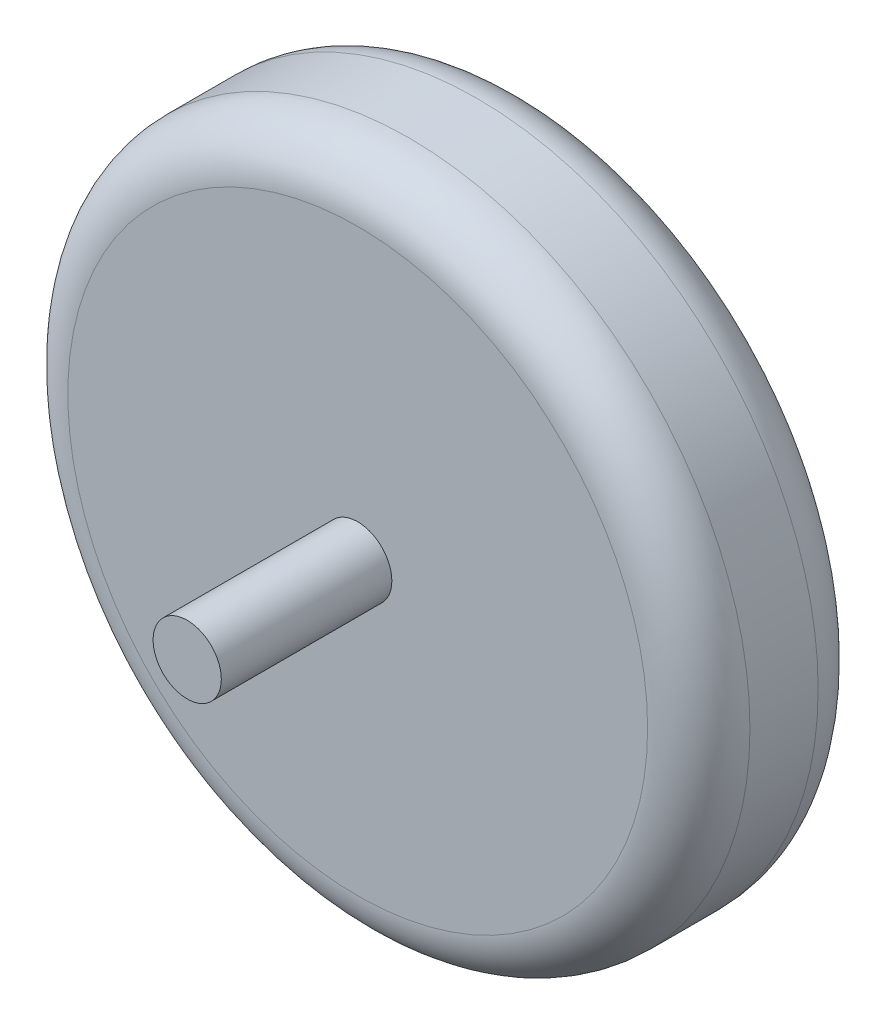
SolidWorks part; units mm, degrees
ref_plane "前视基准面" through (0, 0, 0) normal (0, 0, 1) x (1, 0, 0)
ref_plane "上视基准面" through (0, 0, 0) normal (0, 1, 0) x (1, 0, 0)
ref_plane "右视基准面" through (0, 0, 0) normal (1, 0, 0) x (0, 0, -1)
other "Configuration Table"
sketch "草图1" plane through (0, 0, 0) normal (0, 0, 1) x (1, 0, 0)
  circle A0 centre (0, 0) radius 100
extrude "凸台-拉伸1" add sketch "草图1" along normal blind 50
sketch "草图2" plane through (0, 0, 50) normal (0, 0, 1) x (1, 0, 0)
  circle A0 centre (0, 0) radius 10
extrude "凸台-拉伸2" add sketch "草图2" along normal blind 50
fillet "圆角1" radius 15 2 edges at (100, 0, 0) (100, 0, 50)
